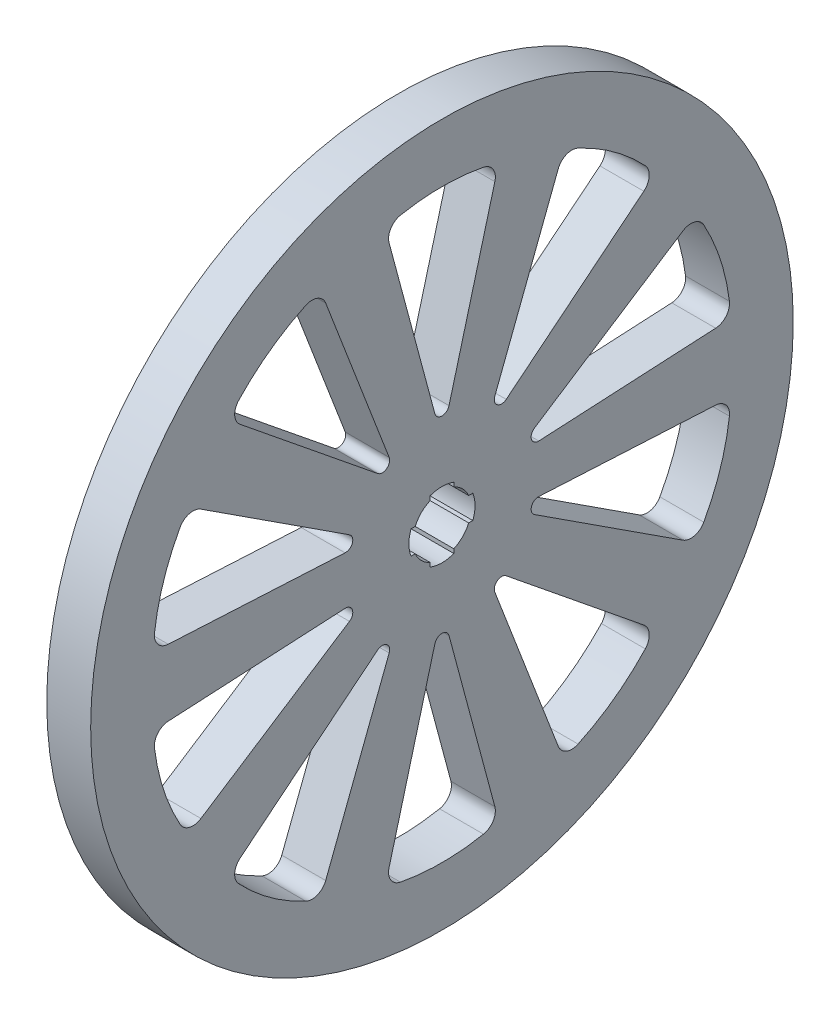
SolidWorks part; units mm, degrees
ref_plane "Front Plane" through (0, 0, 0) normal (0, 0, 1) x (1, 0, 0)
ref_plane "Top Plane" through (0, 0, 0) normal (0, 1, 0) x (1, 0, 0)
ref_plane "Right Plane" through (0, 0, 0) normal (1, 0, 0) x (0, 0, -1)
sketch "Sketch1" plane through (0, 0, 0) normal (1, 0, 0) x (0, 0, -1)
  circle A0 centre (0, 0) radius 24
  dimension "D1" = 48
extrude "Boss-Extrude1" add sketch "Sketch1" along normal blind 3
sketch "Sketch2" plane through (3, 0, 0) normal (1, 0, 0) x (0, 0, -1)
  circle A0 centre (0, 0) radius 2
  dimension "D1" = 4
extrude "Cut-Extrude1" cut sketch "Sketch2" against normal blind 3
sketch "Sketch3" plane through (3, 0, 0) normal (1, 0, 0) x (0, 0, -1)
  line L0 (0, 5) -> (0, 15) construction
  line L1 (0.483, 6.8024) -> (3.6142, 18.4884)
  line L2 (-0.483, 6.8024) -> (-3.6142, 18.4884)
  arc A0 (2.8374, 19.7292) -> (-2.8374, 19.7292) centre (0, 5) ccw
  arc A1 (3.6142, 18.4884) -> (2.8374, 19.7292) centre (2.6483, 18.7472) ccw
  arc A2 (-3.6142, 18.4884) -> (-2.8374, 19.7292) centre (-2.6483, 18.7472) cw
  arc A3 (0.483, 6.8024) -> (-0.483, 6.8024) centre (0, 6.9319) cw
  point P8 (3.8823, 19.4889)
  dimension "D6" = 1
  dimension "D7" = 0.5
  dimension "D1" = 5
  dimension "D2" = 15
  dimension "D3" = 15
  dimension "D4" = 15
  dimension "D5" = 15
extrude "Cut-Extrude2" cut sketch "Sketch3" against normal blind 3
pattern_circular "CirPattern1" count 10 over 360 about axis through (0, 0, 0) along (1, 0, 0) of "Cut-Extrude2"
sketch "Sketch5" plane through (3, 0, 0) normal (1, 0, 0) x (0, 0, -1)
  line L0 (-2.1099, 0.81) -> (-0.81, 0.81)
  line L1 (2.1099, -0.81) -> (-2.1099, -0.81) construction
  line L2 (2.1099, -0.81) -> (2.1099, 0.81) construction
  line L3 (2.1099, 0.81) -> (-2.1099, 0.81) construction
  line L4 (-2.1099, -0.81) -> (-2.1099, 0.81) construction
  line L5 (2.1099, -0.81) -> (-2.1099, 0.81) construction
  line L6 (2.1099, 0.81) -> (-2.1099, -0.81) construction
  line L7 (-0.81, -2.1099) -> (0.81, -2.1099) construction
  line L8 (-0.81, -2.1099) -> (-0.81, 2.1099) construction
  line L9 (-0.81, 2.1099) -> (0.81, 2.1099) construction
  line L10 (0.81, -2.1099) -> (0.81, 2.1099) construction
  line L11 (-0.81, -2.1099) -> (0.81, 2.1099) construction
  line L12 (-0.81, 2.1099) -> (0.81, -2.1099) construction
  line L13 (-0.81, 0.81) -> (-0.81, 2.1099)
  line L14 (0.81, 2.1099) -> (0.81, 0.81)
  line L15 (0.81, 0.81) -> (2.1099, 0.81)
  line L16 (2.1099, -0.81) -> (0.81, -0.81)
  line L17 (0.81, -0.81) -> (0.81, -2.1099)
  line L18 (-0.81, -2.1099) -> (-0.81, -0.81)
  line L19 (-0.81, -0.81) -> (-2.1099, -0.81)
  circle A0 centre (0, 0) radius 2.26 construction
  spline S0 degree 2 poles (-2.1099, -0.81) (-2.4101, 0) (-2.1099, 0.81) knots 0 0 0 1 1 1
  spline S1 degree 2 poles (-0.81, 2.1099) (0, 2.4101) (0.81, 2.1099) knots 0 0 0 1 1 1
  spline S2 degree 2 poles (2.1099, 0.81) (2.4101, 0) (2.1099, -0.81) knots 0 0 0 1 1 1
  spline S3 degree 2 poles (0.81, -2.1099) (0, -2.4101) (-0.81, -2.1099) knots 0 0 0 1 1 1
  dimension "D1" = 4.52
  dimension "D2" = 1.62
  dimension "D3" = 1.62
extrude "Cut-Extrude4" cut sketch "Sketch5" against normal blind 3
equation "\"D1@Sketch5\"=4.70mm-0.18"
